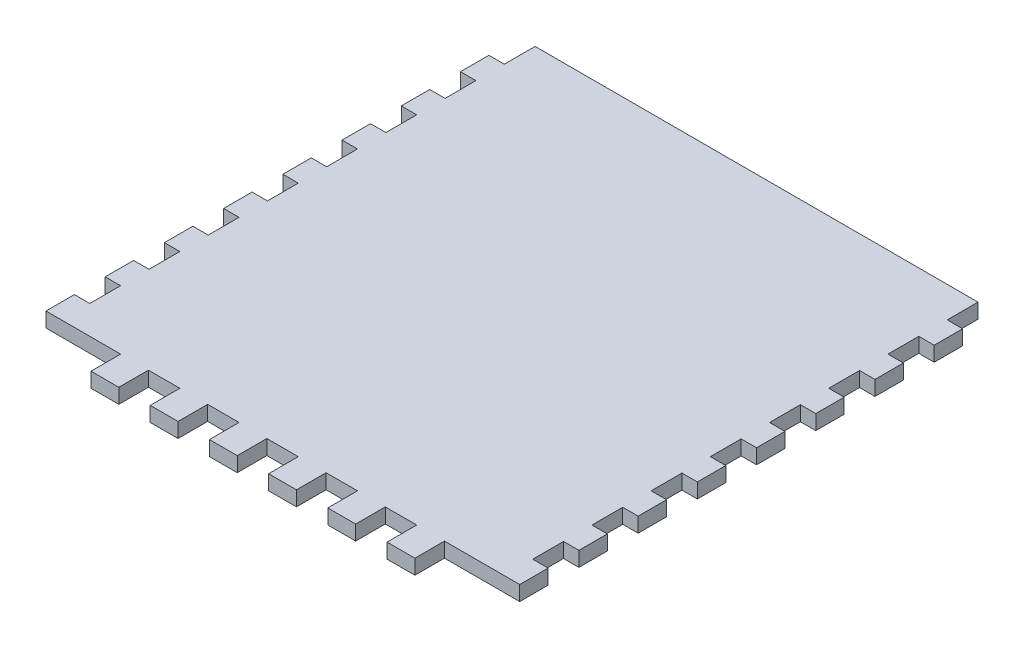
SolidWorks part; units mm, degrees
ref_plane "Front Plane" through (0, 0, 0) normal (0, 0, 1) x (1, 0, 0)
ref_plane "Top Plane" through (0, 0, 0) normal (0, 1, 0) x (1, 0, 0)
ref_plane "Right Plane" through (0, 0, 0) normal (1, 0, 0) x (0, 0, -1)
sketch "Sketch1" plane through (0, 0, 0) normal (0, 1, 0) x (1, 0, 0)
  line L1 (-50.8, -53.975) -> (50.8, -53.975)
  line L2 (-50.8, -53.975) -> (-50.8, 53.975)
  line L3 (-50.8, 53.975) -> (50.8, 53.975)
  line L4 (50.8, -53.975) -> (50.8, 53.975)
  line L5 (-50.8, -53.975) -> (50.8, 53.975) construction
  line L6 (-50.8, 53.975) -> (50.8, -53.975) construction
  point P0 (0, 0)
  dimension "D1" = 101.6
  dimension "D2" = 107.95
extrude "Boss-Extrude1" add sketch "Sketch1" along normal blind 3.175
sketch "Sketch2" plane through (0, 0, 0) normal (0, -1, 0) x (1, 0, 0)
  line L0 (-34.798, 47.625) -> (-47.498, 47.625)
  line L5 (50.8, 53.975) -> (50.8, -53.975) construction
  line L34 (0, 0) -> (0, -14.8721) construction
  line L39 (50.8, 41.529) -> (47.498, 41.529)
  line L41 (50.8, 54.229) -> (50.8, 47.625)
  line L42 (50.8, 47.625) -> (47.498, 47.625)
  line L44 (50.8, 41.529) -> (50.8, 34.925)
  line L45 (50.8, 34.925) -> (47.498, 34.925)
  line L46 (47.498, 41.529) -> (47.498, 34.925)
  line L47 (50.8, 28.829) -> (47.498, 28.829)
  line L48 (50.8, 28.829) -> (50.8, 22.225)
  line L49 (50.8, 22.225) -> (47.498, 22.225)
  line L50 (47.498, 28.829) -> (47.498, 22.225)
  line L51 (50.8, 16.129) -> (47.498, 16.129)
  line L52 (50.8, 16.129) -> (50.8, 9.525)
  line L53 (50.8, 9.525) -> (47.498, 9.525)
  line L54 (47.498, 16.129) -> (47.498, 9.525)
  line L55 (50.8, 3.429) -> (47.498, 3.429)
  line L56 (50.8, 3.429) -> (50.8, -3.175)
  line L57 (50.8, -3.175) -> (47.498, -3.175)
  line L58 (47.498, 3.429) -> (47.498, -3.175)
  line L59 (50.8, -9.271) -> (47.498, -9.271)
  line L60 (50.8, -9.271) -> (50.8, -15.875)
  line L61 (50.8, -15.875) -> (47.498, -15.875)
  line L62 (47.498, -9.271) -> (47.498, -15.875)
  line L63 (50.8, -21.971) -> (47.498, -21.971)
  line L64 (50.8, -21.971) -> (50.8, -28.575)
  line L65 (50.8, -28.575) -> (47.498, -28.575)
  line L66 (47.498, -21.971) -> (47.498, -28.575)
  line L67 (50.8, -34.671) -> (47.498, -34.671)
  line L68 (50.8, -34.671) -> (50.8, -41.275)
  line L69 (50.8, -41.275) -> (47.498, -41.275)
  line L70 (47.498, -34.671) -> (47.498, -41.275)
  line L71 (-47.498, -34.671) -> (-47.498, -41.275)
  line L72 (-50.8, -41.275) -> (-47.498, -41.275)
  line L73 (-50.8, -34.671) -> (-50.8, -41.275)
  line L74 (-50.8, -34.671) -> (-47.498, -34.671)
  line L75 (-47.498, -21.971) -> (-47.498, -28.575)
  line L76 (-50.8, -28.575) -> (-47.498, -28.575)
  line L77 (-50.8, -21.971) -> (-50.8, -28.575)
  line L78 (-50.8, -21.971) -> (-47.498, -21.971)
  line L79 (-47.498, -9.271) -> (-47.498, -15.875)
  line L80 (-50.8, -15.875) -> (-47.498, -15.875)
  line L81 (-50.8, -9.271) -> (-50.8, -15.875)
  line L82 (-50.8, -9.271) -> (-47.498, -9.271)
  line L83 (-47.498, 3.429) -> (-47.498, -3.175)
  line L84 (-50.8, -3.175) -> (-47.498, -3.175)
  line L85 (-50.8, 3.429) -> (-50.8, -3.175)
  line L86 (-50.8, 3.429) -> (-47.498, 3.429)
  line L87 (-47.498, 16.129) -> (-47.498, 9.525)
  line L88 (-50.8, 9.525) -> (-47.498, 9.525)
  line L89 (-50.8, 16.129) -> (-50.8, 9.525)
  line L90 (-50.8, 16.129) -> (-47.498, 16.129)
  line L91 (-47.498, 28.829) -> (-47.498, 22.225)
  line L92 (-50.8, 22.225) -> (-47.498, 22.225)
  line L93 (-50.8, 28.829) -> (-50.8, 22.225)
  line L94 (-50.8, 28.829) -> (-47.498, 28.829)
  line L95 (-47.498, 41.529) -> (-47.498, 34.925)
  line L96 (-50.8, 34.925) -> (-47.498, 34.925)
  line L97 (-50.8, 41.529) -> (-50.8, 34.925)
  line L99 (-50.8, 47.625) -> (-47.498, 47.625)
  line L100 (-50.8, 54.229) -> (-50.8, 47.625)
  line L102 (-50.8, 41.529) -> (-47.498, 41.529)
  line L103 (47.498, 47.625) -> (34.671, 47.625)
  line L104 (34.671, 47.625) -> (34.671, 54.229)
  line L106 (34.671, 54.229) -> (28.702, 54.229)
  line L107 (28.702, 54.229) -> (28.702, 47.625)
  line L108 (28.702, 47.625) -> (21.971, 47.625)
  line L109 (21.971, 47.625) -> (21.971, 54.229)
  line L110 (21.971, 54.229) -> (16.002, 54.229)
  line L111 (16.002, 54.229) -> (16.002, 47.625)
  line L112 (16.002, 47.625) -> (9.271, 47.625)
  line L113 (9.271, 47.625) -> (9.271, 54.229)
  line L114 (9.271, 54.229) -> (3.302, 54.229)
  line L115 (3.302, 54.229) -> (3.302, 47.625)
  line L116 (3.302, 47.625) -> (-3.429, 47.625)
  line L117 (-3.429, 47.625) -> (-3.429, 54.229)
  line L118 (-3.429, 54.229) -> (-9.398, 54.229)
  line L119 (-9.398, 54.229) -> (-9.398, 47.625)
  line L120 (-9.398, 47.625) -> (-16.129, 47.625)
  line L121 (-16.129, 47.625) -> (-16.129, 54.229)
  line L122 (-16.129, 54.229) -> (-22.098, 54.229)
  line L123 (-22.098, 54.229) -> (-22.098, 47.625)
  line L124 (-22.098, 47.625) -> (-28.829, 47.625)
  line L125 (-28.829, 47.625) -> (-28.829, 54.229)
  line L126 (-28.829, 54.229) -> (-34.798, 54.229)
  line L127 (-34.798, 54.229) -> (-34.798, 47.625)
  line L137 (-50.8, 54.229) -> (-50.8, 63.0316)
  line L138 (50.8, -53.975) -> (-50.8, -53.975) construction
  line L139 (-50.8, 63.0316) -> (50.8, 63.0316)
  line L140 (50.8, 63.0316) -> (50.8, 54.229)
  line L141 (50.8, -47.371) -> (50.8, -53.975)
  line L142 (50.8, -53.975) -> (47.498, -53.975)
  line L143 (47.498, -53.975) -> (47.498, -47.371)
  line L144 (47.498, -47.371) -> (50.8, -47.371)
  line L145 (-47.498, -47.371) -> (-50.8, -47.371)
  line L146 (-47.498, -53.975) -> (-47.498, -47.371)
  line L147 (-50.8, -53.975) -> (-47.498, -53.975)
  line L148 (-50.8, -47.371) -> (-50.8, -53.975)
  point P3 (41.0845, 47.625)
  dimension "D1" = 16.129
  dimension "D2" = 6.604
  dimension "D3" = 5.969
  dimension "D4" = 101.6
  dimension "D5" = 28.829
  dimension "D6" = 41.529
  dimension "D7" = 54.229
  dimension "D8" = 3.302
  dimension "D10" = 66.929
  dimension "D11" = 79.629
  dimension "D9" = 9
extrude "Cut-Extrude1" cut sketch "Sketch2" against normal through all
